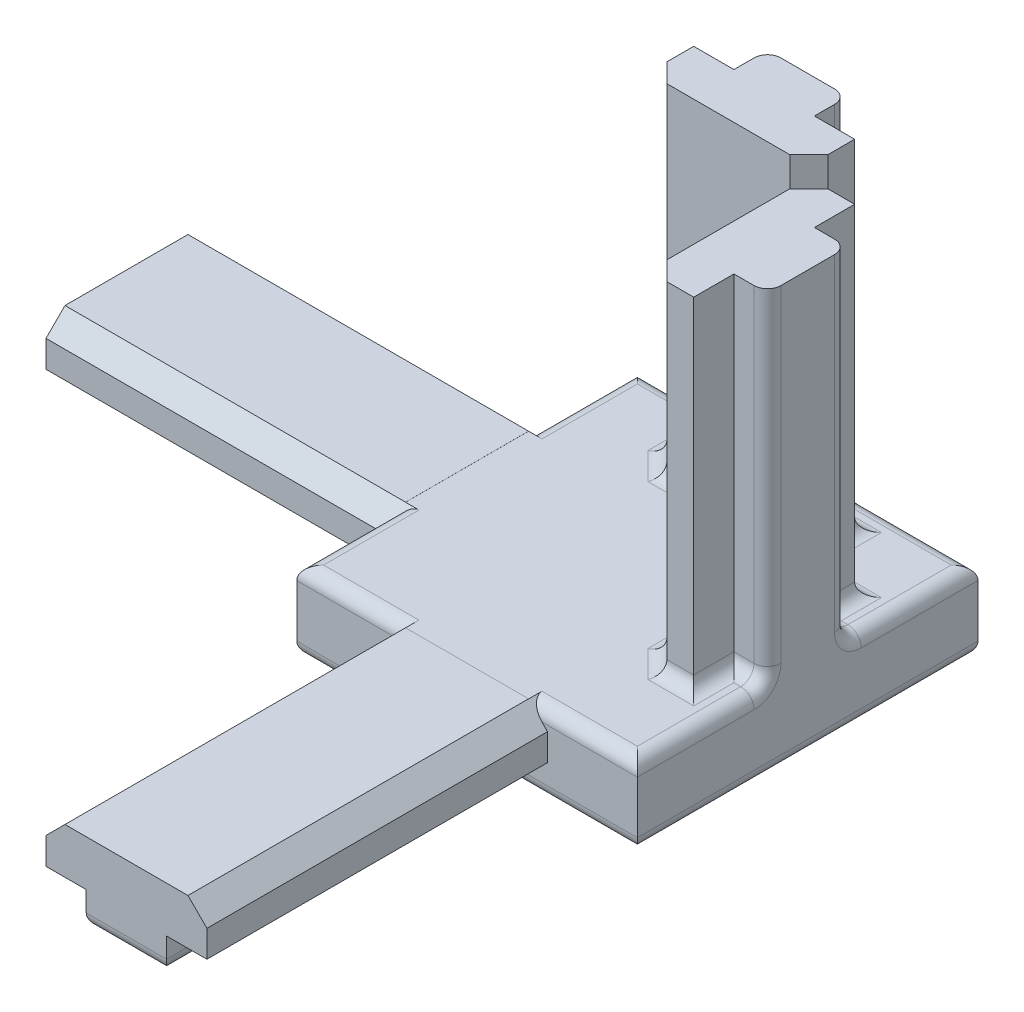
SolidWorks part; units mm, degrees
ref_plane "Front Plane" through (0, 0, 0) normal (0, 0, 1) x (1, 0, 0)
ref_plane "Top Plane" through (0, 0, 0) normal (0, 1, 0) x (1, 0, 0)
ref_plane "Right Plane" through (0, 0, 0) normal (1, 0, 0) x (0, 0, -1)
sketch "Sketch1" plane through (0, 0, 0) normal (0, 1, 0) x (1, 0, 0)
  line L1 (-12.7, 12.7) -> (12.7, 12.7)
  line L2 (-12.7, 12.7) -> (-12.7, -12.7)
  line L3 (-12.7, -12.7) -> (12.7, -12.7)
  line L4 (12.7, 12.7) -> (12.7, -12.7)
  line L5 (-12.7, 12.7) -> (12.7, -12.7) construction
  line L6 (-12.7, -12.7) -> (12.7, 12.7) construction
  point P0 (0, 0)
  dimension "D1" = 25.4
extrude "Boss-Extrude1" add sketch "Sketch1" along normal blind 5.91
sketch "Sketch2" plane through (0, 0, 12.7) normal (0, 0, 1) x (1, 0, 0)
  line L0 (-3, 0) -> (3, 0)
  line L1 (-12.7, 0) -> (12.7, 0) construction
  line L2 (3, 0) -> (3, 2.5)
  line L3 (3, 2.5) -> (6, 2.5)
  line L4 (6, 2.5) -> (6, 4.5)
  line L5 (6, 4.5) -> (4.5858, 5.9142)
  line L6 (4.5858, 5.9142) -> (-4.5858, 5.9142)
  line L7 (0, 0) -> (0, 6.6193) construction
  line L8 (-6, 4.5) -> (-4.5858, 5.9142)
  line L9 (-6, 2.5) -> (-6, 4.5)
  line L10 (-3, 2.5) -> (-6, 2.5)
  line L11 (-3, 0) -> (-3, 2.5)
  point P14 (0, 5.9142)
  point P18 (0, 0)
  dimension "D1" = 6
  dimension "D2" = 12
  dimension "D3" = 135
  dimension "D4" = 2.5
  dimension "D5" = 2
extrude "Boss-Extrude2" add sketch "Sketch2" along normal blind 25.4
sketch "Sketch3" plane through (-12.7, 0, 0) normal (-1, 0, 0) x (0, 0, 1)
  line L0 (-3, 0) -> (3, 0)
  line L1 (3, 0) -> (3, 2.5)
  line L2 (3, 2.5) -> (6, 2.5)
  line L3 (6, 2.5) -> (6, 4.5)
  line L4 (6, 4.5) -> (4.5858, 5.9142)
  line L5 (4.5858, 5.9142) -> (-4.5858, 5.9142)
  line L6 (0, 0) -> (0, 6.6193) construction
  line L7 (-6, 4.5) -> (-4.5858, 5.9142)
  line L8 (-6, 2.5) -> (-6, 4.5)
  line L9 (-3, 2.5) -> (-6, 2.5)
  line L10 (-3, 0) -> (-3, 2.5)
  point P9 (0, 5.9142)
  point P13 (0, 0)
  dimension "D1" = 6
  dimension "D2" = 12
  dimension "D3" = 2.5
  dimension "D4" = 2
  dimension "D5" = 135
extrude "Boss-Extrude3" add sketch "Sketch3" along normal blind 25.4
sketch "Sketch5" plane through (0, 5.91, 0) normal (0, 1, 0) x (1, 0, 0)
  line L0 (3, 12.7) -> (-3, 12.7)
  line L1 (-3, 12.7) -> (-3, 10.2)
  line L2 (-3, 10.2) -> (-6, 10.2)
  line L3 (-6, 10.2) -> (-6, 8.2)
  line L4 (-6, 8.2) -> (-4.5858, 6.7858)
  line L5 (-4.5858, 6.7858) -> (4.5858, 6.7858)
  line L6 (0, 3.4686) -> (0, -3.1261) construction
  line L7 (6, 8.2) -> (4.5858, 6.7858)
  line L8 (6, 10.2) -> (6, 8.2)
  line L9 (3, 10.2) -> (6, 10.2)
  line L10 (3, 12.7) -> (3, 10.2)
  line L11 (12.7, 12.7) -> (-12.7, 12.7) construction
  line L12 (12.7, -3) -> (12.7, 3)
  line L13 (12.7, 3) -> (10.2, 3)
  line L14 (10.2, 3) -> (10.2, 6)
  line L15 (10.2, 6) -> (8.2, 6)
  line L16 (8.2, 6) -> (6.7858, 4.5858)
  line L17 (6.7858, 4.5858) -> (6.7858, -4.5858)
  line L18 (6.7858, 0) -> (12.7, 0) construction
  line L19 (8.2, -6) -> (6.7858, -4.5858)
  line L20 (10.2, -6) -> (8.2, -6)
  line L21 (10.2, -3) -> (10.2, -6)
  line L22 (12.7, -3) -> (10.2, -3)
  line L23 (12.7, -12.7) -> (12.7, 12.7) construction
  point P9 (0, 6.7858)
  point P13 (0, 12.7)
  point P27 (6.7858, 0)
  point P31 (12.7, 0)
  dimension "D1" = 6
  dimension "D2" = 12
  dimension "D3" = 2.5
  dimension "D4" = 2
  dimension "D5" = 135
  dimension "D6" = 2.5
  dimension "D7" = 6
  dimension "D8" = 12
  dimension "D9" = 2
  dimension "D10" = 135
  dimension "D11" = 135
extrude "Boss-Extrude4" add sketch "Sketch5" along normal blind 25.4
fillet "Fillet2" radius 1 42 edges at (3, 18.61, -12.7) (12.7, 18.61, -3) (12.7, 18.61, 3) (-3, 18.61, -12.7) (-6, 5.91, -9.2) (-5.2929, 5.91, -7.4929) (0, 5.91, -6.7858) (5.2929, 5.91, -7.4929) (6, 5.91, -9.2) (4.5, 5.91, -10.2) (3, 5.91, -11.45) (7.85, 5.91, -12.7) (12.7, 5.91, -7.85) (11.45, 5.91, -3) (10.2, 5.91, -4.5) (9.2, 5.91, -6) (7.4929, 5.91, -5.2929) (6.7858, 5.91, 0) (7.4929, 5.91, 5.2929) (9.2, 5.91, 6) (10.2, 5.91, 4.5) (11.45, 5.91, 3) (12.7, 5.91, 7.85) (8.645, 5.91, 12.7) (-8.645, 5.91, 12.7) (-12.7, 5.91, 8.645) (-12.7, 5.91, -8.645) (-7.85, 5.91, -12.7) (-3, 5.91, -11.45) (-4.5, 5.91, -10.2) (0, 0, -12.7) (-12.7, 0, -7.85) (-25.4, 0, -3) (-38.1, 0, 0) (-25.4, 0, 3) (-12.7, 0, 7.85) (-7.85, 0, 12.7) (-3, 0, 25.4) (0, 0, 38.1) (3, 0, 25.4) (7.85, 0, 12.7) (12.7, 0, 0)
equation "\"Insert Lengths\"= 1in"
equation "\"D1@Boss-Extrude2\"=\"Insert Lengths\""
equation "\"D1@Boss-Extrude4\"=\"Insert Lengths\""
